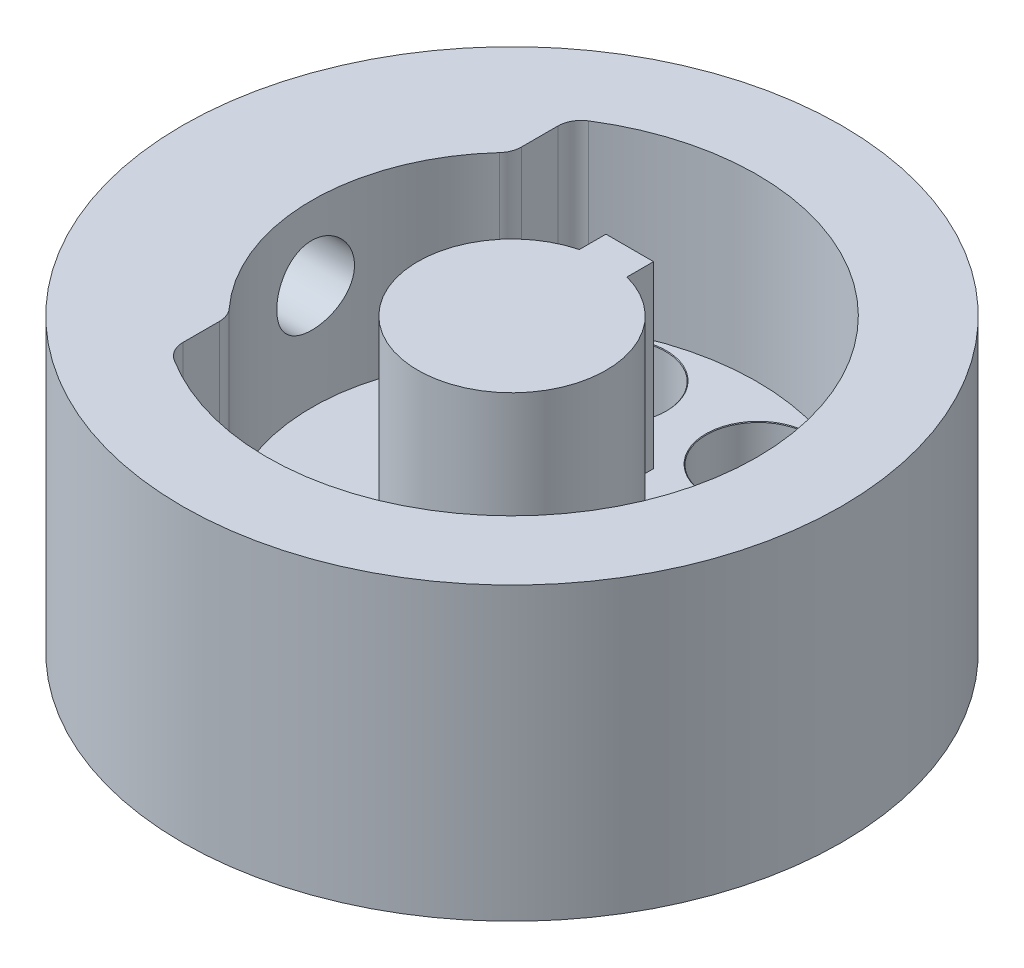
SolidWorks part; units mm, degrees
ref_plane "Front Plane" through (0, 0, 0) normal (0, 0, 1) x (1, 0, 0)
ref_plane "Top Plane" through (0, 0, 0) normal (0, 1, 0) x (1, 0, 0)
ref_plane "Right Plane" through (0, 0, 0) normal (1, 0, 0) x (0, 0, -1)
sketch "Sketch1" plane through (0, 0, 0) normal (0, 1, 0) x (1, 0, 0)
  line L0 (0, 8) -> (0, -8) construction
  line L1 (7.391, 3.0615) -> (-3.0615, 7.391) construction
  line L2 (7.391, 3.0615) -> (3.0615, -7.391) construction
  line L3 (3.0615, -7.391) -> (-7.391, -3.0615) construction
  line L4 (-3.0615, 7.391) -> (-7.391, -3.0615) construction
  line L5 (7.391, 3.0615) -> (-7.391, -3.0615) construction
  line L6 (3.0615, -7.391) -> (-3.0615, 7.391) construction
  line L7 (-8, 0) -> (8, 0) construction
  line L9 (3.0615, 7.391) -> (-7.391, 3.0615) construction
  line L10 (3.0615, 7.391) -> (7.391, -3.0615) construction
  line L11 (7.391, -3.0615) -> (-3.0615, -7.391) construction
  line L12 (-7.391, 3.0615) -> (-3.0615, -7.391) construction
  line L13 (3.0615, 7.391) -> (-3.0615, -7.391) construction
  line L14 (7.391, -3.0615) -> (-7.391, 3.0615) construction
  circle A0 centre (0, 0) radius 14
  circle A1 centre (0, 0) radius 8 construction
  dimension "D1" = 28
  dimension "D2" = 16
  dimension "D3" = 22.5
  dimension "D4" = 22.5
  dimension "D5" = 90
extrude "Boss-Extrude1" add sketch "Sketch1" against normal blind 4.75 contours A0
sketch "Sketch4" plane through (0, 0, 0) normal (0, 1, 0) x (1, 0, 0)
  line L1 (1.01, 5) -> (-1.01, 5)
  line L2 (1.01, 5) -> (1.01, 3.8704)
  line L3 (1.01, 3.8704) -> (-1.01, 3.8704)
  line L4 (-1.01, 5) -> (-1.01, 3.8704)
  line L5 (1.01, 5) -> (-1.01, 3.8704) construction
  line L6 (1.01, 3.8704) -> (-1.01, 5) construction
  circle A0 centre (0, 0) radius 4
  point P3 (0, 4.4352)
  dimension "D1" = 8
  dimension "D2" = 1.1296
  dimension "D3" = 2.02
extrude "Boss-Extrude4" add sketch "Sketch4" along normal blind 7.6142 contours L3 A0 | A0 L2 L1 L4 | L3 A0
sketch "Sketch5" plane through (0, 0, 0) normal (0, 1, 0) x (1, 0, 0)
  line L0 (0, 0) -> (-9.8995, 9.8995)
  line L1 (0, 0) -> (-9.8995, -9.8995)
  line L2 (0, 0) -> (-14, 0) construction
  line L3 (-6.0104, 12.6442) -> (-6.0104, 6.0104)
  line L4 (-6.0104, -6.0104) -> (-6.0104, -12.6442)
  circle A0 centre (0, 0) radius 8.5
  circle A1 centre (0, 0) radius 14
  circle A2 centre (0, 0) radius 14 construction
  circle A3 centre (0, 0) radius 10.4
  circle M5 centre (0, 0) radius 14
  dimension "D1" = 17
  dimension "D2" = 20.8
  dimension "D3" = 45
  dimension "D4" = 45
extrude "Boss-Extrude5" add sketch "Sketch5" along normal blind 7.6142 contours L2 A0 L0 A1 | A0 L2 A1 L1 | L3 L0 M5 | L4 L1 M5 | L2 A3 L0 M5 | A3 L2 A1 L1 | L3 A3 L0 | L1 A3 L4 | A3 L4 L3 M5
ref_plane "Plane1" through (-20, 0, 0) normal (1, 0, 0) x (0, 0, -1)
sketch "Sketch11" plane through (-20, 0, 0) normal (1, 0, 0) x (0, 0, -1)
  line L0 (0, 4.4892) -> (0, 7.6142) construction
  line L1 (14, 7.6142) -> (-14, 7.6142) construction
  circle A0 centre (0, 4.4892) radius 2 construction
  dimension "D2" = 4
  dimension "D1" = 3.125
hole_wizard "Tap Drill for M4x0.7 Tap2" positions "Sketch15" profile "Sketch17" hole size "M4x0.7" standard "ANSI Metric"
sketch "Sketch15" plane through (-20, 0, 0) normal (1, 0, 0) x (0, 0, -1)
  point P0 (0, 4.4892)
sketch "Sketch17" plane through (-20, 4.4892, 0) normal (0, 1, 0) x (0, 0, 1)
  line L0 (0, 0) -> (0, 14.7404)
  line L1 (0, 14.7404) -> (1.65, 13.749)
  line L2 (1.65, 13.749) -> (1.65, 0.025)
  line L3 (1.65, 0.025) -> (1.675, 0)
  line L5 (1.675, 0) -> (0, 0)
  line L6 (-1.65, 0.025) -> (-1.675, 0) construction
  line L10 (0, 14.7404) -> (-1.65, 13.749) construction
  line L11 (0, -6.35) -> (0, 107.95) construction
  dimension "Hole Dia." = 3.3
  dimension "Hole Depth" = 13.749
  dimension "Near C'Sink Dia." = 3.35
  dimension "Near C'Sink Angle" = 90
  dimension "Drill Angle" = 118
fillet "Fillet2" radius 1 4 edges at (-6.0104, 3.8071, 8.4873) (-6.0104, 3.8071, 6.0104) (-6.0104, 3.8071, -6.0104) (-6.0104, 3.8071, -8.4873)
hole_wizard "CBORE for M2 SHCS3" positions "Sketch18" profile "Sketch19" counterbore size "M2" standard "ANSI Metric"
sketch "Sketch18" plane through (0, 0, 0) normal (0, 1, 0) x (1, 0, 0)
  point P0 (-3.0615, 7.391)
  point P3 (3.0615, 7.391)
  point P6 (7.391, 3.0615)
  point P9 (7.391, -3.0615)
  point P12 (3.0615, -7.391)
  point P15 (-3.0615, -7.391)
sketch "Sketch19" plane through (-3.0615, 0, -7.391) normal (1, 0, 0) x (0, 0, 1)
  line L0 (0, 0) -> (0, 5.471)
  line L1 (0, 5.471) -> (1.2, 4.75)
  line L2 (1.2, 4.75) -> (1.2, 3.5)
  line L3 (1.2, 3.5) -> (2.2, 3.5)
  line L5 (2.2, 3.5) -> (2.2, 0.025)
  line L6 (2.2, 0.025) -> (2.225, 0)
  line L7 (2.225, 0) -> (0, 0)
  line L8 (-2.2, 0.025) -> (-2.225, 0) construction
  line L10 (0, 5.471) -> (-1.2, 4.75) construction
  line L11 (0, -6.35) -> (0, 107.95) construction
  dimension "Hole Dia." = 2.4
  dimension "Hole Depth" = 4.75
  dimension "C'Bore Dia." = 4.4
  dimension "C'Bore Depth" = 3.5
  dimension "Near C'Sink Dia." = 4.45
  dimension "Near C'Sink Angle" = 90
  dimension "Drill Angle" = 118
sketch "Sketch20" plane through (0, -4.75, 0) normal (0, -1, 0) x (1, 0, 0)
  circle A0 centre (0, 0) radius 4
  dimension "D1" = 8
extrude "Cut-Extrude2" cut sketch "Sketch20" against normal blind 2.75 contours A0
sketch "Sketch21" plane through (0, -2, 0) normal (0, -1, 0) x (-1, 0, 0)
  circle A0 centre (0, 0) radius 2
  dimension "D1" = 4
extrude "Cut-Extrude3" cut sketch "Sketch21" against normal blind 2.5
